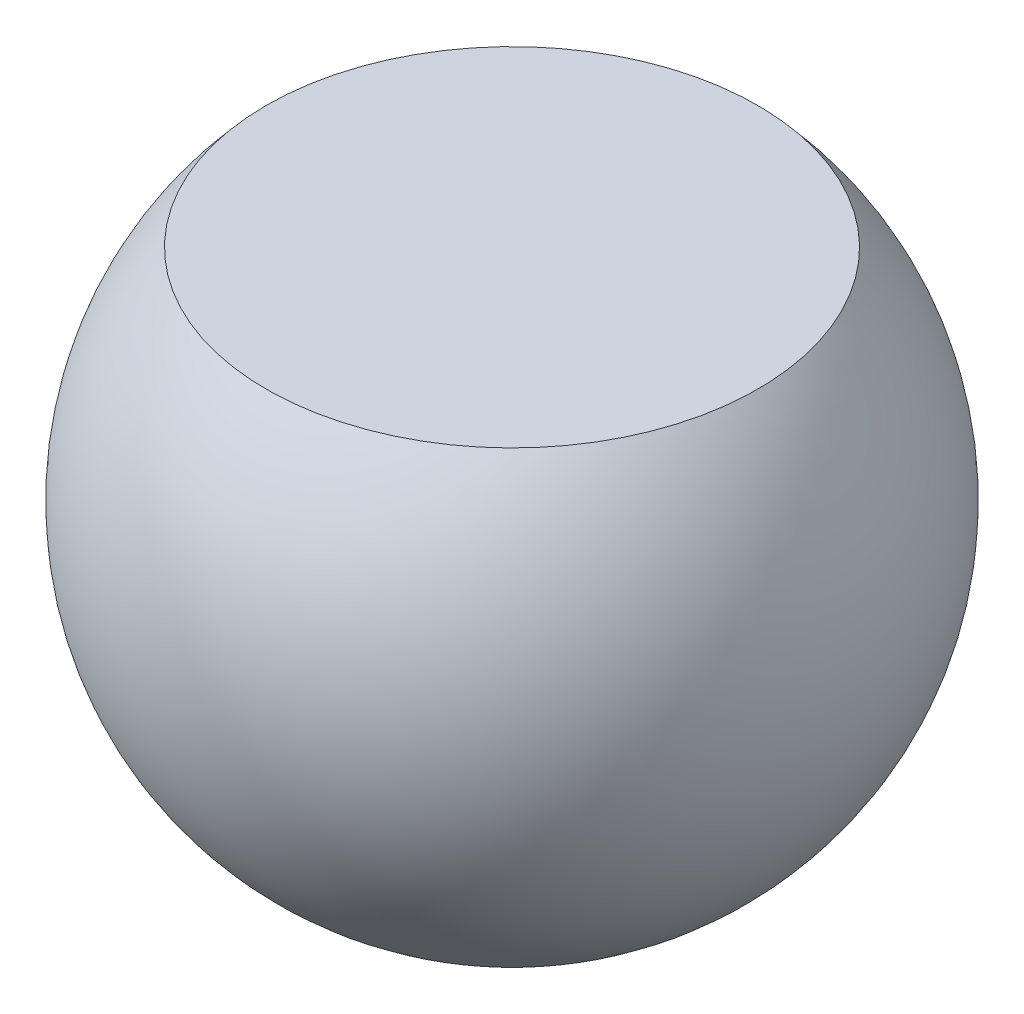
SolidWorks part; units mm, degrees
ref_plane "前视基准面" through (0, 0, 0) normal (0, 0, 1) x (1, 0, 0)
ref_plane "上视基准面" through (0, 0, 0) normal (0, 1, 0) x (1, 0, 0)
ref_plane "右视基准面" through (0, 0, 0) normal (1, 0, 0) x (0, 0, -1)
sketch "草图1" plane through (0, 0, 0) normal (0, 0, 1) x (1, 0, 0)
  line L0 (0, 6) -> (6.7082, 6)
  line L1 (0, 6) -> (0, -9)
  arc A0 (0, -9) -> (6.7082, 6) centre (0, 0) ccw
  point P5 (6.7082, 6)
  point P6 (1.5794, -8.8603)
  dimension "D1" = 18
  dimension "D2" = 6
revolve "旋转1" add sketch "草图1" angle 360 about L1
